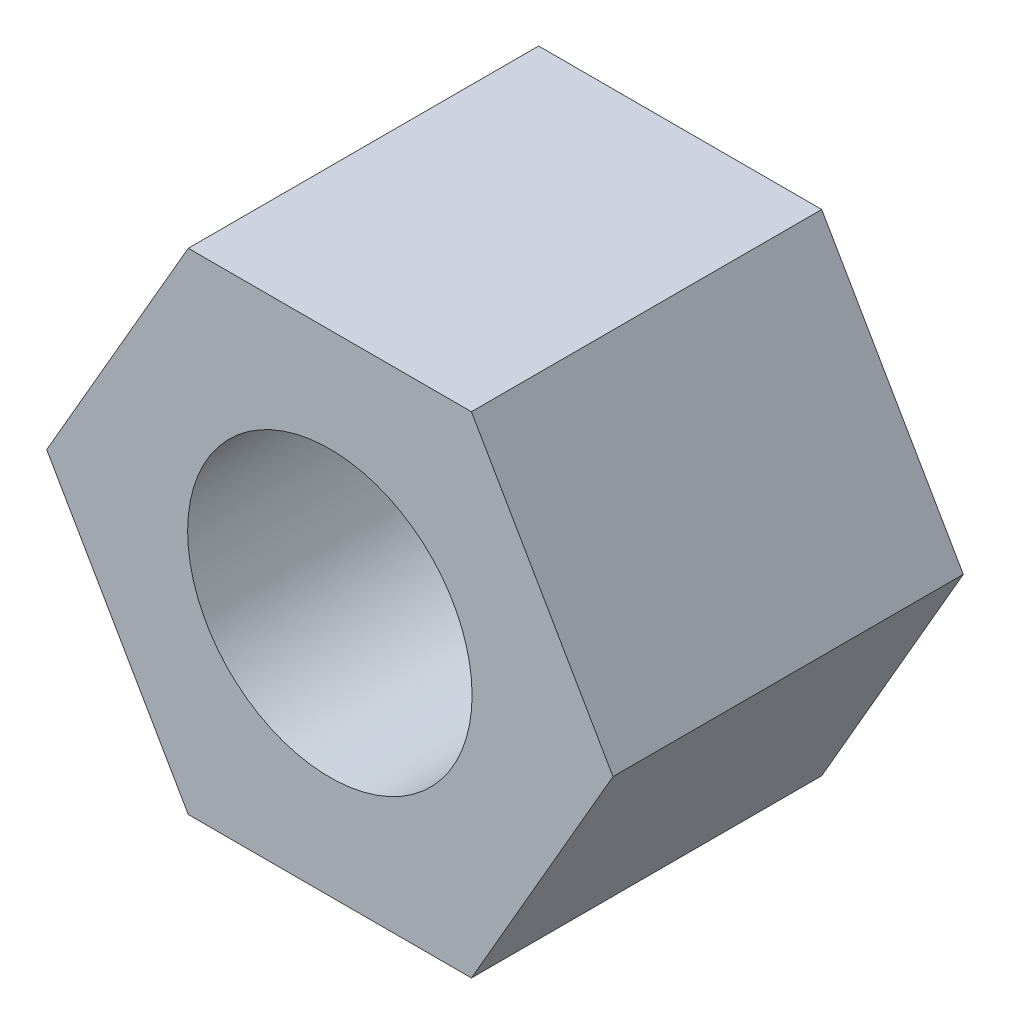
SolidWorks part; units mm, degrees
ref_plane "Front Plane" through (0, 0, 0) normal (0, 0, 1) x (1, 0, 0)
ref_plane "Top Plane" through (0, 0, 0) normal (0, 1, 0) x (1, 0, 0)
ref_plane "Right Plane" through (0, 0, 0) normal (1, 0, 0) x (0, 0, -1)
sketch "S01 - Hexagon and nominal thread envelope" plane through (0, 0, 0) normal (0, 0, 1) x (1, 0, 0)
  line L0 (4.0415, 0) -> (2.0207, 3.5)
  line L1 (2.0207, 3.5) -> (-2.0207, 3.5)
  line L2 (-2.0207, 3.5) -> (-4.0415, 0)
  line L3 (-4.0415, 0) -> (-2.0207, -3.5)
  line L4 (-2.0207, -3.5) -> (2.0207, -3.5)
  line L5 (2.0207, -3.5) -> (4.0415, 0)
  circle A0 centre (0, 0) radius 2.03
  dimension "D1" = 4.06
  dimension "D2" = 2.0207
  dimension "D3" = 4.0415
  dimension "D4" = 2.0207
  dimension "D5" = 4.0415
  dimension "D6" = 3.5
  dimension "D7" = 3.5
extrude "01 - Hexagon and nominal thread envelope" add sketch "S01 - Hexagon and nominal thread envelope" along normal blind 5
